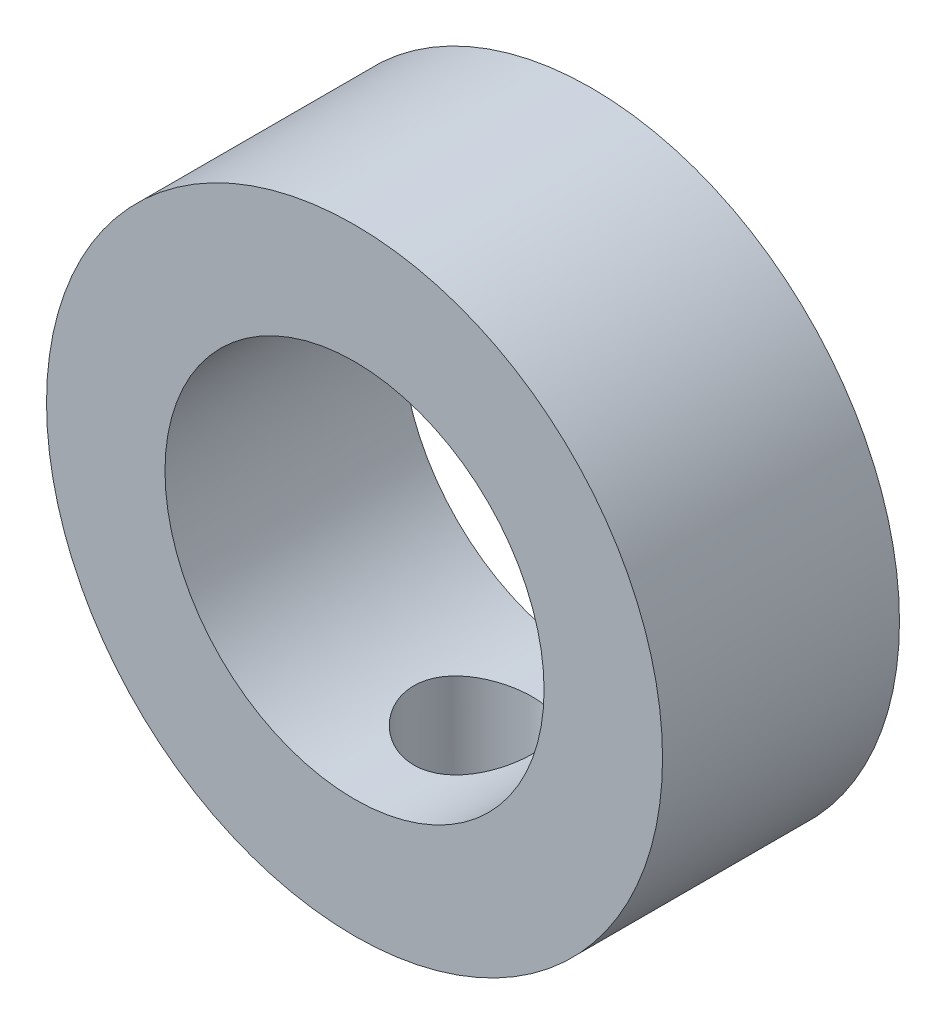
SolidWorks part; units mm, degrees
ref_plane "Front Plane" through (0, 0, 0) normal (0, 0, 1) x (1, 0, 0)
ref_plane "Top Plane" through (0, 0, 0) normal (0, 1, 0) x (1, 0, 0)
ref_plane "Right Plane" through (0, 0, 0) normal (1, 0, 0) x (0, 0, -1)
sketch "Sketch1" plane through (0, 0, 0) normal (0, 0, 1) x (1, 0, 0)
  circle A0 centre (0, 0) radius 4
  circle A1 centre (0, 0) radius 6.5
  dimension "D1" = 8
  dimension "D2" = 13
extrude "Boss-Extrude1" add sketch "Sketch1" along normal blind 5
sketch "Sketch2" plane through (0, 0, 0) normal (0, 1, 0) x (1, 0, 0)
  line L0 (4, 0) -> (-4, 0) construction
  circle A0 centre (0, -2.5) radius 1.25
  dimension "D2" = 2.5
  dimension "D1" = 2.5
extrude "Cut-Extrude1" cut sketch "Sketch2" against normal through all
sketch "Sketch3" plane through (0, 0, 5) normal (0, 0, 1) x (1, 0, 0)
  line L0 (0, 0) -> (0, 8.9466)
